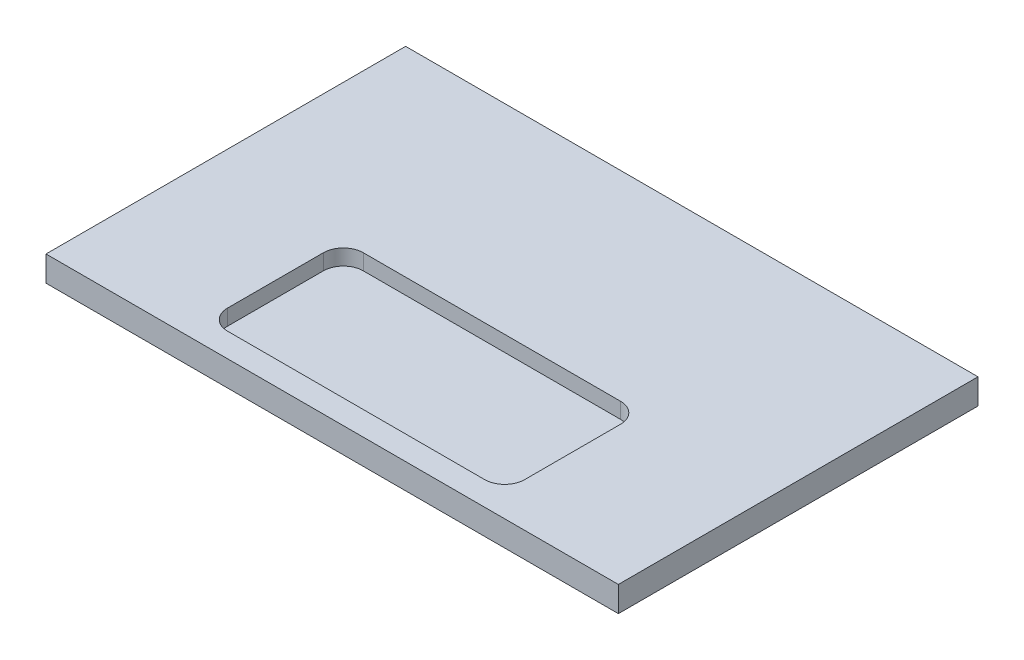
SolidWorks part; units mm, degrees
ref_plane "Front Plane" through (0, 0, 0) normal (0, 0, 1) x (1, 0, 0)
ref_plane "Top Plane" through (0, 0, 0) normal (0, 1, 0) x (1, 0, 0)
ref_plane "Right Plane" through (0, 0, 0) normal (1, 0, 0) x (0, 0, -1)
sketch "Sketch1" plane through (0, 0, 0) normal (0, 1, 0) x (1, 0, 0)
  line L0 (-192.1968, 11.8239) -> (94.8232, 11.8239)
  line L1 (94.8232, 11.8239) -> (94.8232, -168.5161)
  line L2 (94.8232, -168.5161) -> (-192.1968, -168.5161)
  line L3 (-192.1968, -168.5161) -> (-192.1968, 11.8239)
  dimension "D1" = 287.02
  dimension "D2" = 180.34
extrude "Boss-Extrude3" add sketch "Sketch1" along normal blind 12.7
sketch "Sketch3" plane through (0, 12.7, 0) normal (0, 1, 0) x (1, 0, 0)
  line L0 (-123.1868, -156.5161) -> (-123.1868, -88.4161)
  line L1 (-123.1868, -88.4161) -> (25.8132, -88.4161)
  line L2 (25.8132, -88.4161) -> (25.8132, -156.5161)
  line L3 (25.8132, -156.5161) -> (-123.1868, -156.5161)
  line L4 (-192.1968, -168.5161) -> (94.8232, -168.5161) construction
  dimension "D1" = 68.1
  dimension "D2" = 149
  dimension "D3" = 12
extrude "Cut-Extrude1" cut sketch "Sketch3" against normal blind 7.874
fillet "Fillet1" radius 10 4 edges at (25.8132, 8.763, 156.5161) (25.8132, 8.763, 88.4161) (-123.1868, 8.763, 156.5161) (-123.1868, 8.763, 88.4161)
sketch "Sketch5" plane through (0, 12.7, 0) normal (0, 1, 0) x (1, 0, 0)
  line L0 (-122.1868, -68.4161) -> (-122.1868, -57.0161)
  line L1 (-122.1868, -57.0161) -> (-110.1868, -57.0161)
  line L2 (-110.1868, -57.0161) -> (-110.1868, -68.4161)
  line L3 (-110.1868, -68.4161) -> (-122.1868, -68.4161)
  line L4 (-95.1868, -68.4161) -> (-107.1868, -68.4161)
  line L5 (-107.1868, -68.4161) -> (-107.1868, -57.0161)
  line L6 (-107.1868, -57.0161) -> (-95.1868, -57.0161)
  line L7 (-95.1868, -57.0161) -> (-95.1868, -68.4161)
  line L8 (-80.1868, -68.4161) -> (-92.1868, -68.4161)
  line L9 (-92.1868, -68.4161) -> (-92.1868, -57.0161)
  line L10 (-92.1868, -57.0161) -> (-80.1868, -57.0161)
  line L11 (-80.1868, -57.0161) -> (-80.1868, -68.4161)
  line L12 (-65.1868, -68.4161) -> (-77.1868, -68.4161)
  line L13 (-77.1868, -68.4161) -> (-77.1868, -57.0161)
  line L14 (-77.1868, -57.0161) -> (-65.1868, -57.0161)
  line L15 (-65.1868, -57.0161) -> (-65.1868, -68.4161)
  line L16 (-50.1868, -68.4161) -> (-62.1868, -68.4161)
  line L17 (-62.1868, -68.4161) -> (-62.1868, -57.0161)
  line L18 (-62.1868, -57.0161) -> (-50.1868, -57.0161)
  line L19 (-50.1868, -57.0161) -> (-50.1868, -68.4161)
  line L20 (-35.1868, -68.4161) -> (-47.1868, -68.4161)
  line L21 (-47.1868, -68.4161) -> (-47.1868, -57.0161)
  line L22 (-47.1868, -57.0161) -> (-35.1868, -57.0161)
  line L23 (-35.1868, -57.0161) -> (-35.1868, -68.4161)
  line L24 (-20.1868, -68.4161) -> (-32.1868, -68.4161)
  line L25 (-32.1868, -68.4161) -> (-32.1868, -57.0161)
  line L26 (-32.1868, -57.0161) -> (-20.1868, -57.0161)
  line L27 (-20.1868, -57.0161) -> (-20.1868, -68.4161)
  line L28 (-5.1868, -68.4161) -> (-17.1868, -68.4161)
  line L29 (-17.1868, -68.4161) -> (-17.1868, -57.0161)
  line L30 (-17.1868, -57.0161) -> (-5.1868, -57.0161)
  line L31 (-5.1868, -57.0161) -> (-5.1868, -68.4161)
  line L32 (9.8132, -68.4161) -> (-2.1868, -68.4161)
  line L33 (-2.1868, -68.4161) -> (-2.1868, -57.0161)
  line L34 (-2.1868, -57.0161) -> (9.8132, -57.0161)
  line L35 (9.8132, -57.0161) -> (9.8132, -68.4161)
  line L36 (24.8132, -68.4161) -> (12.8132, -68.4161)
  line L37 (12.8132, -68.4161) -> (12.8132, -57.0161)
  line L38 (12.8132, -57.0161) -> (24.8132, -57.0161)
  line L39 (24.8132, -57.0161) -> (24.8132, -68.4161)
  line L40 (-110.1868, -68.4161) -> (-95.1868, -68.4161) construction
  line L41 (-122.1868, -62.7161) -> (-192.1968, -62.7161)
  line L42 (-192.1968, 11.8239) -> (-192.1968, -168.5161) construction
  line L43 (24.8132, -62.7161) -> (94.8232, -62.7161)
  line L44 (94.8232, -168.5161) -> (94.8232, 11.8239) construction
  line L45 (15.8132, -88.4161) -> (-113.1868, -88.4161) construction
  line L47 (-53.5447, -85.6434) -> (-53.5447, -74.7707)
  line L48 (-53.5447, -74.7707) -> (18.4553, -74.7707)
  line L49 (18.4553, -74.7707) -> (18.4553, -85.6434)
  line L50 (18.4553, -85.6434) -> (-53.5447, -85.6434)
  point P45 (-122.1868, -62.7161)
  dimension "D1" = 12
  dimension "D2" = 11.4
  dimension "D4" = 15
  dimension "D5" = 20
  dimension "D6" = 72
  dimension "D3" = 10
